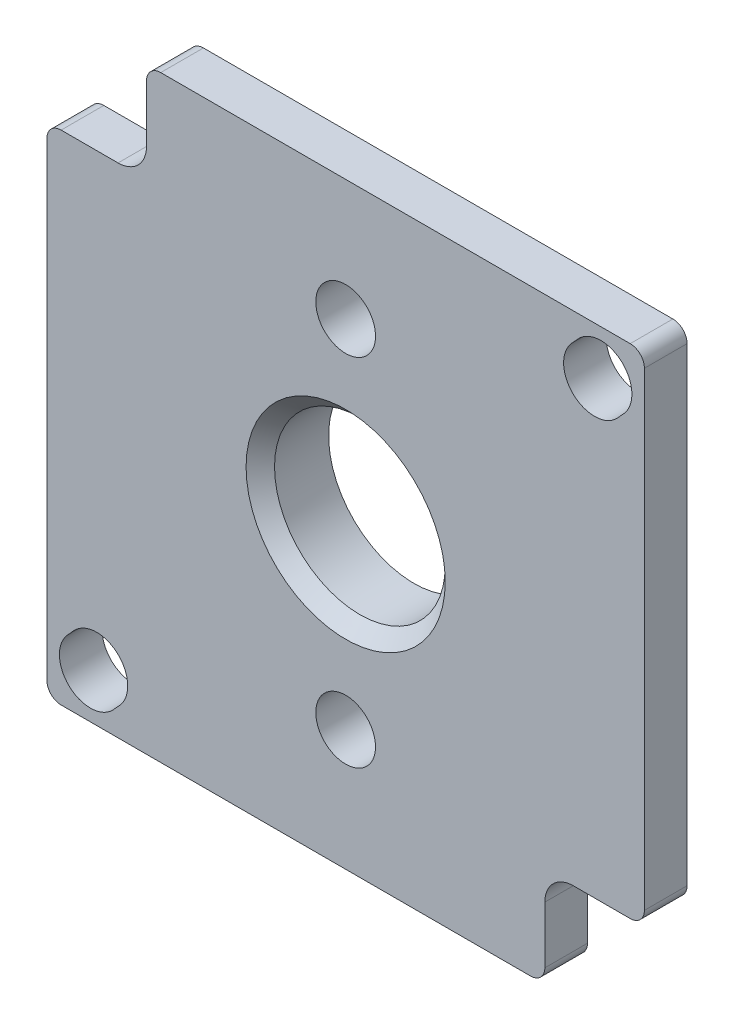
SolidWorks part; units mm, degrees
ref_plane "Front Plane" through (0, 0, 0) normal (0, 0, 1) x (1, 0, 0)
ref_plane "Top Plane" through (0, 0, 0) normal (0, 1, 0) x (1, 0, 0)
ref_plane "Right Plane" through (0, 0, 0) normal (1, 0, 0) x (0, 0, -1)
ref_plane "Plane1" through (0, 0, -1.5) normal (0, 0, -1) x (-1, 0, 0)
sketch "Sketch1" plane through (0, 0, -1.5) normal (0, 0, -1) x (-1, 0, 0)
  line L0 (21, -21) -> (21, 21)
  line L1 (21, 21) -> (-21, 21)
  line L2 (-21, 21) -> (-21, -21)
  line L3 (-21, -21) -> (21, -21)
extrude "Boss-Extrude1" add sketch "Sketch1" against normal blind 3
sketch "Sketch2" plane through (0, 0, 1.5) normal (0, 0, 1) x (1, 0, 0)
  line L0 (14, -14) -> (14, -21)
  line L1 (14, -21) -> (21, -21)
  line L2 (21, -21) -> (21, -14)
  line L3 (21, -14) -> (14, -14)
extrude "Cut-Extrude1" cut sketch "Sketch2" against normal through all
sketch "Sketch3" plane through (0, 0, 1.5) normal (0, 0, 1) x (1, 0, 0)
  line L0 (-21, 14) -> (-14, 14)
  line L1 (-14, 14) -> (-14, 21)
  line L2 (-14, 21) -> (-21, 21)
  line L3 (-21, 21) -> (-21, 14)
extrude "Cut-Extrude2" cut sketch "Sketch3" against normal through all
sketch "Sketch4" plane through (0, 0, -1.5) normal (0, 0, -1) x (-1, 0, 0)
  line L0 (-19.5481, 16.5087) -> (-19.1079, 16.0279)
  line L1 (-15.8921, 18.9721) -> (-16.3323, 19.4529)
  arc A0 (-19.1079, 16.0279) -> (-15.8921, 18.9721) centre (-17.5, 17.5) ccw
  arc A1 (-16.3323, 19.4529) -> (-19.5481, 16.5087) centre (-17.9402, 17.9808) ccw
extrude "Cut-Extrude3" cut sketch "Sketch4" against normal through all
sketch "Sketch5" plane through (0, 0, 1.5) normal (0, 0, 1) x (1, 0, 0)
  line L0 (-16.3323, -19.4529) -> (-15.8921, -18.9721)
  line L1 (-19.1079, -16.0279) -> (-19.5481, -16.5087)
  arc A0 (-19.5481, -16.5087) -> (-16.3323, -19.4529) centre (-17.9402, -17.9808) ccw
  arc A1 (-15.8921, -18.9721) -> (-19.1079, -16.0279) centre (-17.5, -17.5) ccw
extrude "Cut-Extrude4" cut sketch "Sketch5" against normal through all
sketch "Sketch6" plane through (0, 0, -1.5) normal (0, 0, -1) x (-1, 0, 0)
  arc A0 (5.0542, -14.0166) -> (3.7223, -12.9547) centre (4.715, -13.0759) cw
  arc A1 (3.7223, -12.9547) -> (-3.7223, -12.9547) centre (0, -12.5) ccw
  arc A2 (-3.7223, -12.9547) -> (-5.0542, -14.0166) centre (-4.715, -13.0759) cw
  arc A3 (-5.0542, -14.0166) -> (-5.0542, 14.0166) centre (0, 0) cw
  arc A4 (-5.0542, 14.0166) -> (-3.7223, 12.9547) centre (-4.715, 13.0759) cw
  arc A5 (-3.7223, 12.9547) -> (3.7223, 12.9547) centre (0, 12.5) ccw
  arc A6 (3.7223, 12.9547) -> (5.0542, 14.0166) centre (4.715, 13.0759) cw
  arc A7 (5.0542, 14.0166) -> (5.0542, -14.0166) centre (0, 0) cw
extrude "Boss-Extrude2" add sketch "Sketch6" along normal blind 1.8
sketch "Sketch7" plane through (0, 0, -3.3) normal (0, 0, -1) x (-1, 0, 0)
  line L0 (12.18, -5.5863) -> (7.1852, -3.5174)
  arc A0 (3.7874, -7.0467) -> (3.5791, -8.6591) centre (4.2608, -7.9275) ccw
  arc A1 (3.5791, -8.6591) -> (5.2472, -12.3299) centre (0, -12.5) cw
  arc A2 (5.2472, -12.3299) -> (12.18, -5.5863) centre (0, 0) ccw
  arc A3 (7.1852, -3.5174) -> (3.7874, -7.0467) centre (0, 0) cw
extrude "Cut-Extrude5" cut sketch "Sketch7" against normal blind 1.8
sketch "Sketch8" plane through (0, 0, -3.3) normal (0, 0, -1) x (-1, 0, 0)
  line L0 (-12.18, 5.5863) -> (-7.1852, 3.5174)
  arc A0 (-3.7874, 7.0467) -> (-3.5791, 8.6591) centre (-4.2608, 7.9275) ccw
  arc A1 (-3.5791, 8.6591) -> (-5.2472, 12.3299) centre (0, 12.5) cw
  arc A2 (-5.2472, 12.3299) -> (-12.18, 5.5863) centre (0, 0) ccw
  arc A3 (-7.1852, 3.5174) -> (-3.7874, 7.0467) centre (0, 0) cw
extrude "Cut-Extrude6" cut sketch "Sketch8" against normal blind 1.8
sketch "Sketch9" plane through (0, 0, -3.3) normal (0, 0, -1) x (-1, 0, 0)
  line L0 (-7.1852, -3.5174) -> (-12.18, -5.5863)
  arc A0 (-3.5791, -8.6591) -> (-3.7874, -7.0467) centre (-4.2608, -7.9275) ccw
  arc A1 (-3.7874, -7.0467) -> (-7.1852, -3.5174) centre (0, 0) cw
  arc A2 (-12.18, -5.5863) -> (-5.2472, -12.3299) centre (0, 0) ccw
  arc A3 (-5.2472, -12.3299) -> (-3.5791, -8.6591) centre (0, -12.5) cw
extrude "Cut-Extrude7" cut sketch "Sketch9" against normal blind 1.8
sketch "Sketch10" plane through (0, 0, -3.3) normal (0, 0, -1) x (-1, 0, 0)
  line L0 (7.1852, 3.5174) -> (12.18, 5.5863)
  arc A0 (3.5791, 8.6591) -> (3.7874, 7.0467) centre (4.2608, 7.9275) ccw
  arc A1 (3.7874, 7.0467) -> (7.1852, 3.5174) centre (0, 0) cw
  arc A2 (12.18, 5.5863) -> (5.2472, 12.3299) centre (0, 0) ccw
  arc A3 (5.2472, 12.3299) -> (3.5791, 8.6591) centre (0, 12.5) cw
extrude "Cut-Extrude8" cut sketch "Sketch10" against normal blind 1.8
sketch "Sketch11" plane through (0, 0, -3.3) normal (0, 0, -1) x (-1, 0, 0)
  line L0 (12.5627, 4.6624) -> (7.5679, 2.5935)
  line L1 (7.5679, -2.5935) -> (12.5627, -4.6624)
  arc A0 (12.5627, -4.6624) -> (12.5627, 4.6624) centre (0, 0) ccw
  arc A1 (7.5679, 2.5935) -> (7.5679, -2.5935) centre (0, 0) cw
extrude "Cut-Extrude9" cut sketch "Sketch11" against normal blind 1.8
sketch "Sketch12" plane through (0, 0, -3.3) normal (0, 0, -1) x (-1, 0, 0)
  line L0 (-12.5627, -4.6624) -> (-7.5679, -2.5935)
  line L1 (-7.5679, 2.5935) -> (-12.5627, 4.6624)
  arc A0 (-12.5627, 4.6624) -> (-12.5627, -4.6624) centre (0, 0) ccw
  arc A1 (-7.5679, -2.5935) -> (-7.5679, 2.5935) centre (0, 0) cw
extrude "Cut-Extrude10" cut sketch "Sketch12" against normal blind 1.8
hole_wizard "#6 Clearance Hole1" positions "Sketch14" profile "Sketch13" hole size "#6" standard "ANSI Inch"
sketch "Sketch14" plane through (0, 0, -1.5) normal (0, 0, -1) x (-1, 0, 0)
  point P0 (0, -12.5)
  point P1 (0, 12.5)
sketch "Sketch13" plane through (0, -12.5, -1.5) normal (1, 0, 0) x (0, 1, 0)
  line L0 (0, 0) -> (0, 3)
  line L1 (0, 3) -> (2.1, 3)
  line L2 (2.1, 3) -> (2.1, 0)
  line L5 (2.1, 0) -> (0, 0)
  line L11 (0, -6.35) -> (0, 107.95) construction
  dimension "Thru Hole Dia." = 4.2
  dimension "Thru Hole Depth" = 3
hole_wizard "7/16 Clearance Hole1" positions "Sketch16" profile "Sketch15" hole size "7/16" standard "ANSI Inch"
sketch "Sketch16" plane through (0, 0, 1.5) normal (0, 0, 1) x (1, 0, 0)
  point P0 (0, 0)
sketch "Sketch15" plane through (0, 0, 1.5) normal (1, 0, 0) x (0, -1, 0)
  line L0 (0, 0) -> (0, 4.8)
  line L1 (0, 4.8) -> (6, 4.8)
  line L2 (6, 4.8) -> (6, 0)
  line L5 (6, 0) -> (0, 0)
  line L11 (0, -6.35) -> (0, 107.95) construction
  dimension "Thru Hole Dia." = 12
  dimension "Thru Hole Depth" = 4.8
chamfer "Chamfer1" distance 1 angle 45 1 edges at (6, 0, 1.5)
chamfer "Chamfer2" distance 0.5 angle 45 8 edges at (14.9, 0, -3.3) (4.0915, -13.8578, -3.3) (4.0915, 13.8578, -3.3) (0, -8.75, -3.3) (0, 8.75, -3.3) (-4.0915, -13.8578, -3.3) (-4.0915, 13.8578, -3.3) (-14.9, 0, -3.3)
fillet "Fillet1" radius 1 26 edges at (5.2472, 12.3299, -2.4) (-12.18, -5.5863, -2.4) (-21, 14, 0) (7.1852, 3.5174, -2.4) (-12.18, 5.5863, -2.4) (12.18, 5.5863, -2.4) (-5.2472, 12.3299, -2.4) (7.1852, -3.5174, -2.4) (14, -21, 0) (12.18, -5.5863, -2.4) (-7.1852, 3.5174, -2.4) (-7.5679, 2.5935, -2.4) (-5.2472, -12.3299, -2.4) (-12.5627, 4.6624, -2.4) (5.2472, -12.3299, -2.4) (-12.5627, -4.6624, -2.4) (-14, 21, 0) (7.5679, -2.5935, -2.4) (-21, -21, 0) (12.5627, -4.6624, -2.4) (21, 21, 0) (21, -14, 0) (-7.1852, -3.5174, -2.4) (12.5627, 4.6624, -2.4) (7.5679, 2.5935, -2.4) (-7.5679, -2.5935, -2.4)
fillet "Fillet2" radius 2 2 edges at (14, -14, 0) (-14, 14, 0)
